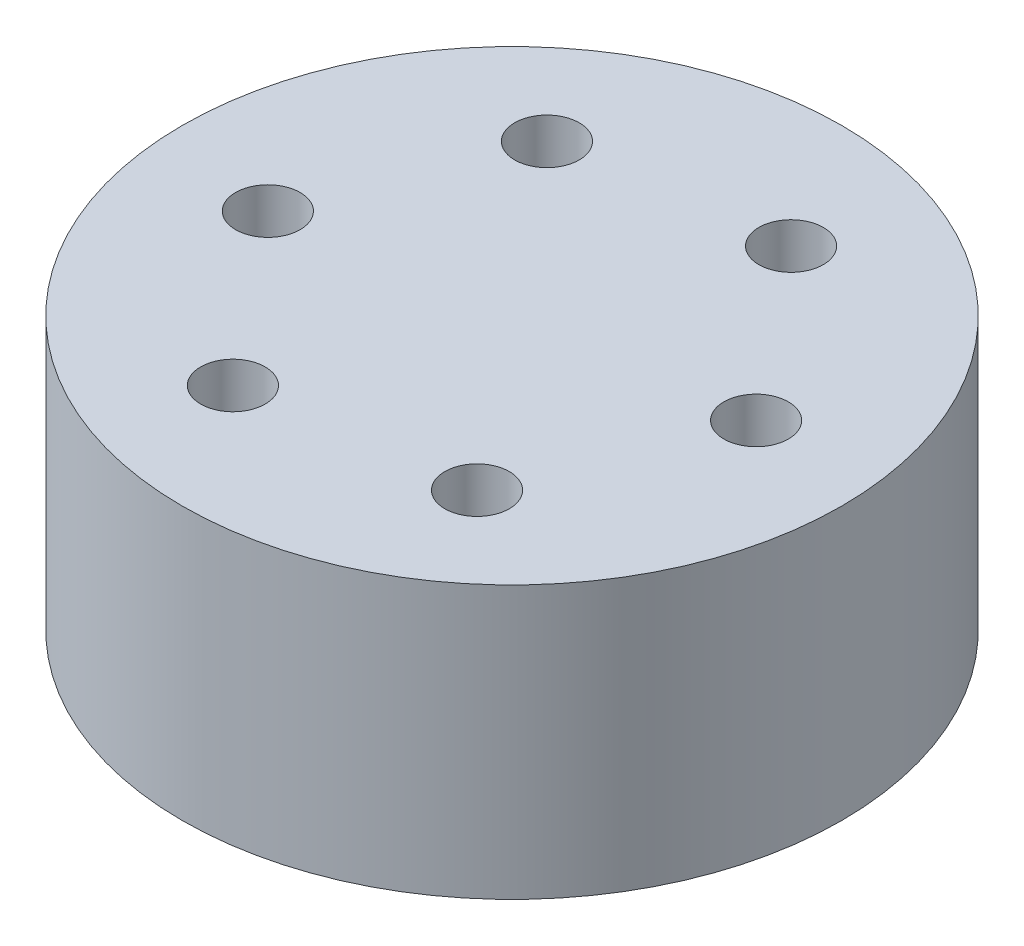
SolidWorks part; units mm, degrees
material "Aleación 6061"
ref_plane "Alzado" through (0, 0, 0) normal (0, 0, 1) x (1, 0, 0)
ref_plane "Planta" through (0, 0, 0) normal (0, 1, 0) x (1, 0, 0)
ref_plane "Vista lateral" through (0, 0, 0) normal (1, 0, 0) x (0, 0, -1)
sketch "Sk_Cubo" plane through (0, 0, 0) normal (0, 1, 0) x (1, 0, 0)
  circle A0 centre (0, -170) radius 23
  dimension "D1" = 46
  dimension "D2" = 170
extrude "Cubo" add sketch "Sk_Cubo" along normal blind 19 from offset 27.75
sketch "Sk_Pasantes_M4" plane through (0, 0, 0) normal (0, 1, 0) x (1, 0, 0)
  circle A0 centre (14.8391, -167.8088) radius 2.25
  circle A1 centre (9.3172, -181.7554) radius 2.25
  circle A2 centre (-5.5219, -183.9466) radius 2.25
  circle A3 centre (-14.8391, -172.1912) radius 2.25
  circle A4 centre (-9.3172, -158.2446) radius 2.25
  circle A5 centre (5.5219, -156.0534) radius 2.25
  dimension "D1" = 4.5
  dimension "D4" = 4.5
  dimension "D7" = 4.5
  dimension "D10" = 4.5
  dimension "D13" = 4.5
  dimension "D16" = 4.5
  dimension "D2" = 14.8391
  dimension "D3" = 167.8088
  dimension "D5" = 9.3172
  dimension "D6" = 181.7554
  dimension "D8" = 5.5219
  dimension "D9" = 183.9466
  dimension "D11" = 14.8391
  dimension "D12" = 172.1912
  dimension "D14" = 9.3172
  dimension "D15" = 158.2446
  dimension "D17" = 5.5219
  dimension "D18" = 156.0534
extrude "Pasantes_M4" cut sketch "Sk_Pasantes_M4" along normal blind 19 from offset 27.75
sketch "Sk_Centrador_D42" plane through (0, 0, 0) normal (0, 1, 0) x (1, 0, 0)
  circle A0 centre (0, -170) radius 21.2
  dimension "D1" = 42.4
  dimension "D2" = 170
extrude "Centrador_D42" cut sketch "Sk_Centrador_D42" along normal blind 1.2 from offset 27.75
sketch "Sk_Pasadores_motor" plane through (0, 0, 0) normal (0, 1, 0) x (1, 0, 0)
  circle A0 centre (13.2958, -175.2642) radius 2.6
  circle A1 centre (-11.2068, -178.8824) radius 2.6
  circle A2 centre (-2.089, -155.8534) radius 2.6
  dimension "D1" = 5.2
  dimension "D4" = 5.2
  dimension "D7" = 5.2
  dimension "D2" = 13.2958
  dimension "D3" = 175.2642
  dimension "D5" = 11.2068
  dimension "D6" = 178.8824
  dimension "D8" = 2.089
  dimension "D9" = 155.8534
extrude "Pasadores_motor" cut sketch "Sk_Pasadores_motor" along normal blind 5 from offset 27.75
